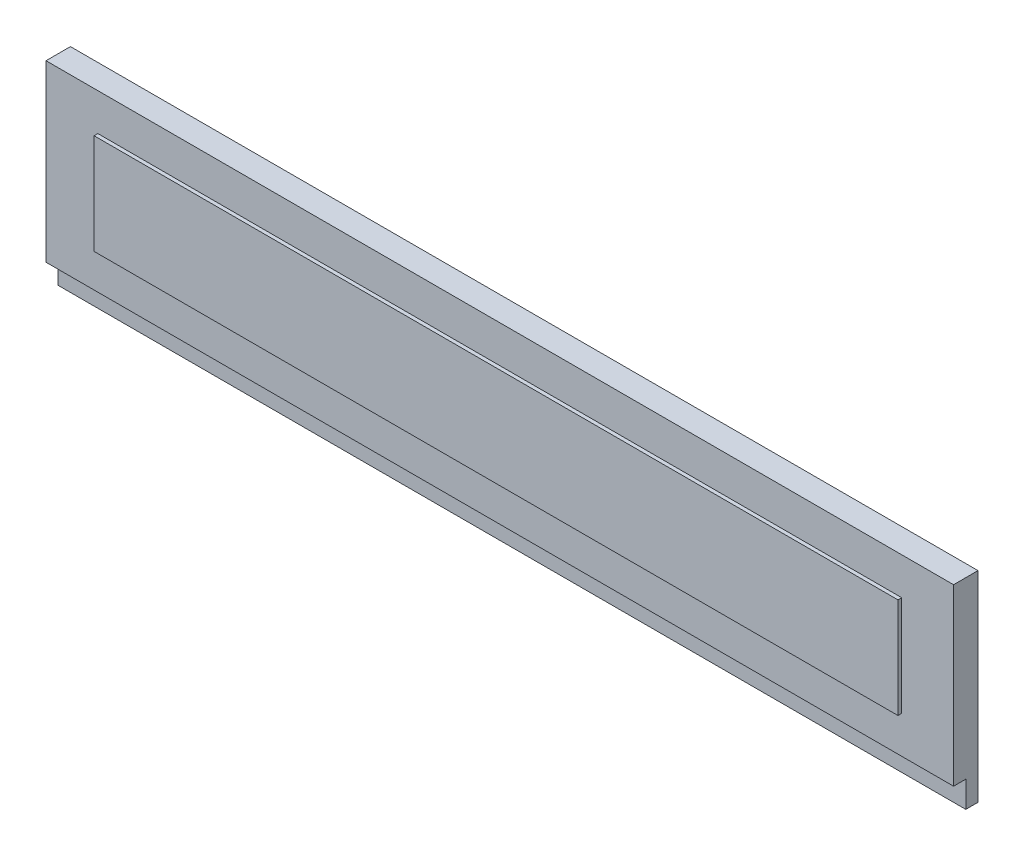
SolidWorks part; units mm, degrees
ref_plane "Front Plane" through (0, 0, 0) normal (0, 0, 1) x (1, 0, 0)
ref_plane "Top Plane" through (0, 0, 0) normal (0, 1, 0) x (1, 0, 0)
ref_plane "Right Plane" through (0, 0, 0) normal (1, 0, 0) x (0, 0, -1)
sketch "Sketch1" plane through (0, 0, 0) normal (0, 0, 1) x (1, 0, 0)
  line L1 (-26, -5.75) -> (26, -5.75)
  line L2 (-26, -5.75) -> (-26, 5.75)
  line L3 (-26, 5.75) -> (26, 5.75)
  line L4 (26, -5.75) -> (26, 5.75)
  line L5 (-26, -5.75) -> (26, 5.75) construction
  line L6 (-26, 5.75) -> (26, -5.75) construction
  point P0 (0, 0)
  dimension "D1" = 52
  dimension "D2" = 11.5
extrude "Boss-Extrude1" add sketch "Sketch1" along normal blind 0.7
sketch "Sketch2" plane through (0, 0, 0.7) normal (0, 0, 1) x (1, 0, 0)
  line L0 (26, -5.75) -> (26, 5.75) construction
  line L1 (-26, 5.75) -> (26, 5.75)
  line L2 (-26, 5.75) -> (-26, -4.25)
  line L3 (-26, -4.25) -> (26, -4.25)
  line L4 (26, 5.75) -> (26, -4.25)
  dimension "D1" = 10
extrude "Boss-Extrude2" add sketch "Sketch2" along normal blind 0.7
sketch "Sketch3" plane through (0, 0, 1.4) normal (0, 0, 1) x (1, 0, 0)
  line L0 (0, 5.75) -> (0, -4.25) construction
  line L1 (26, 5.75) -> (-26, 5.75) construction
  line L2 (-26, -4.25) -> (26, -4.25) construction
  line L4 (-23.03, 3.62) -> (23.03, 3.62)
  line L5 (-23.03, 3.62) -> (-23.03, -2.12)
  line L6 (-23.03, -2.12) -> (23.03, -2.12)
  line L7 (23.03, 3.62) -> (23.03, -2.12)
  line L8 (-23.03, 3.62) -> (23.03, -2.12) construction
  line L9 (-23.03, -2.12) -> (23.03, 3.62) construction
  point P6 (0, 0.75)
  dimension "D1" = 5.74
  dimension "D2" = 46.06
extrude "Boss-Extrude3" add sketch "Sketch3" along normal blind 0.215
sketch "Sketch4" plane through (0, 0, 0) normal (0, 0, -1) x (-1, 0, 0)
  line L0 (0, 3.62) -> (0, -2.12) construction
  line L2 (-25.5, -3.5) -> (25.5, -3.5)
  line L3 (-25.5, -3.5) -> (-25.5, 5)
  line L4 (-23.03, 3.62) -> (-23.03, -2.12)
  line L5 (23.03, 3.62) -> (-23.03, 3.62)
  line L6 (23.03, -2.12) -> (23.03, 3.62)
  line L7 (-23.03, -2.12) -> (23.03, -2.12)
  line L8 (-23.03, 3.62) -> (-23.03, -2.12) construction
  line L9 (23.03, 3.62) -> (-23.03, 3.62) construction
  line L10 (23.03, -2.12) -> (23.03, 3.62) construction
  line L11 (-23.03, -2.12) -> (23.03, -2.12) construction
  line L12 (-25.5, 5) -> (25.5, 5)
  line L13 (25.5, -3.5) -> (25.5, 5)
  line L14 (-25.5, -3.5) -> (25.5, 5) construction
  line L15 (-25.5, 5) -> (25.5, -3.5) construction
  point P6 (0, 0.75)
  dimension "D2" = 8.5
  dimension "D3" = 51
  dimension "D1" = 0
extrude "Boss-Extrude4" add sketch "Sketch4" along normal blind 0.215
